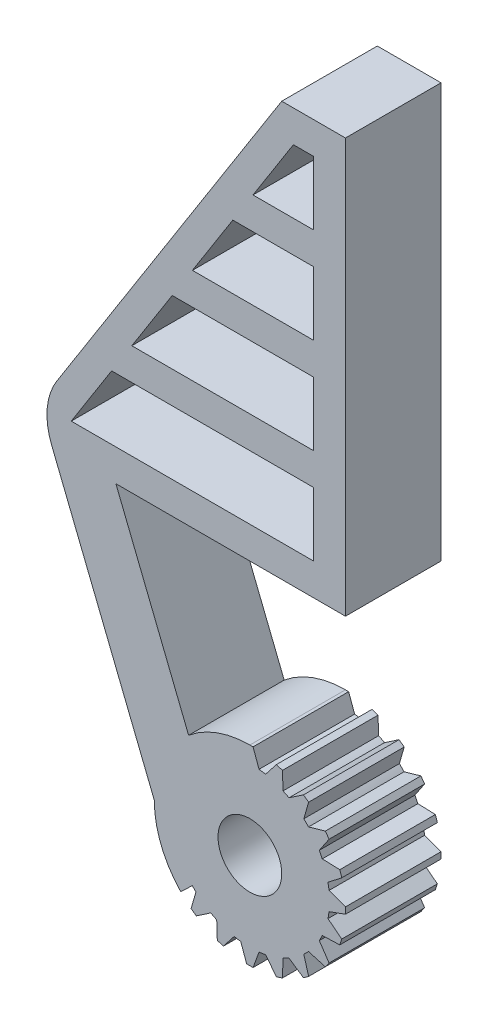
SolidWorks part; units mm, degrees
ref_plane "Front Plane" through (0, 0, 0) normal (0, 0, 1) x (1, 0, 0)
ref_plane "Top Plane" through (0, 0, 0) normal (0, 1, 0) x (1, 0, 0)
ref_plane "Right Plane" through (0, 0, 0) normal (1, 0, 0) x (0, 0, -1)
sketch "Sketch1" plane through (0, 0, 0) normal (0, 0, 1) x (1, 0, 0)
  line L0 (0, 0) -> (0, -120) construction
  line L1 (0, 0) -> (0, -10)
  line L2 (0, -50) -> (0, -60)
  line L5 (-48.033, -60) -> (-30, -105)
  line L7 (-36.0294, -65) -> (-20, -105)
  line L9 (-30, -105) -> (-20, -105)
  line L10 (0, 0) -> (0, -60)
  line L11 (-5, -60) -> (-43.033, -60)
  line L12 (0, 0) -> (-10, 0)
  line L13 (-8.1694, -5) -> (-14.5083, -15)
  line L14 (-5, -5) -> (-5, -15)
  line L15 (-5, -15) -> (-14.5083, -15)
  line L16 (-5, -20) -> (-5, -30)
  line L17 (-17.6777, -20) -> (-5, -20)
  line L18 (-24.0165, -30) -> (-5, -30)
  line L19 (-10, 0) -> (-48.033, -60)
  line L20 (-5, -50) -> (-5, -60)
  line L21 (-5, -35) -> (-27.1859, -35)
  line L22 (-33.5248, -45) -> (-5, -45)
  line L23 (-5, -5) -> (-8.1694, -5)
  line L24 (-5, -50) -> (-36.6942, -50)
  line L25 (0, -60) -> (0, -65)
  line L26 (0, -65) -> (-46.0294, -65)
  line L27 (-17.6777, -20) -> (-24.0165, -30)
  line L28 (-5, -35) -> (-5, -45)
  line L29 (-27.1859, -35) -> (-33.5248, -45)
  line L30 (-36.6942, -50) -> (-43.033, -60)
  circle A2 centre (-15, -105) radius 15
  circle A3 centre (-15, -105) radius 5
  point P27 (-9.7541, -15)
  dimension "D2" = 5
  dimension "D5" = 15
  dimension "D6" = 15
  dimension "D4" = 120
  dimension "D7" = 5
  dimension "D8" = 15
  dimension "D11" = 5
  dimension "D12" = 5
extrude "Boss-Extrude1" add sketch "Sketch1" along normal blind 15
sketch "Sketch2" plane through (0, 0, 15) normal (0, 0, 1) x (1, 0, 0)
  line L0 (-15, -90) -> (-15, -92.5)
  line L1 (-25.8458, -115.3619) -> (-24.0381, -113.6349)
  arc A0 (-25.8458, -115.3619) -> (-15, -90) centre (-15, -105) ccw
  arc A1 (-24.0381, -113.6349) -> (-15, -92.5) centre (-15, -105) ccw
  dimension "D1" = 2.5
  dimension "D2" = 30
extrude "Cut-Extrude1" cut sketch "Sketch2" against normal blind 15
sketch "Sketch3" plane through (0, 0, 15) normal (0, 0, 1) x (1, 0, 0)
  line L0 (-15, -90) -> (-14.5, -90)
  line L3 (-15, -92.75) -> (-15, -90)
  line L4 (-15, -92.75) -> (-13.5, -92.75)
  line L5 (-13.5, -92.75) -> (-14.5, -90)
  line L7 (-12.6411, -92.886) -> (-9.788, -93.8131)
  line L8 (-9.788, -93.8131) -> (-9.8892, -90.8887)
  line L9 (-10.8403, -90.5796) -> (-9.8892, -90.8887)
  line L10 (-12.6411, -92.886) -> (-10.8403, -90.5796)
  line L11 (-9.0132, -94.2079) -> (-6.5861, -95.9712)
  line L12 (-6.5861, -95.9712) -> (-5.7787, -93.1586)
  line L13 (-6.5877, -92.5709) -> (-5.7787, -93.1586)
  line L14 (-9.0132, -94.2079) -> (-6.5877, -92.5709)
  line L15 (-5.9712, -96.5861) -> (-4.2079, -99.0132)
  line L16 (-4.2079, -99.0132) -> (-2.5709, -96.5877)
  line L17 (-3.1586, -95.7787) -> (-2.5709, -96.5877)
  line L18 (-5.9712, -96.5861) -> (-3.1586, -95.7787)
  line L19 (-3.8131, -99.788) -> (-2.886, -102.6411)
  line L20 (-2.886, -102.6411) -> (-0.5796, -100.8403)
  line L21 (-0.8887, -99.8892) -> (-0.5796, -100.8403)
  line L22 (-3.8131, -99.788) -> (-0.8887, -99.8892)
  line L23 (-2.75, -103.5) -> (-2.75, -106.5)
  line L24 (-2.75, -106.5) -> (0, -105.5)
  line L25 (0, -104.5) -> (0, -105.5)
  line L26 (-2.75, -103.5) -> (0, -104.5)
  line L27 (-2.886, -107.3589) -> (-3.8131, -110.212)
  line L28 (-3.8131, -110.212) -> (-0.8887, -110.1108)
  line L29 (-0.5796, -109.1597) -> (-0.8887, -110.1108)
  line L30 (-2.886, -107.3589) -> (-0.5796, -109.1597)
  line L31 (-4.2079, -110.9868) -> (-5.9712, -113.4139)
  line L32 (-5.9712, -113.4139) -> (-3.1586, -114.2213)
  line L33 (-2.5709, -113.4123) -> (-3.1586, -114.2213)
  line L34 (-4.2079, -110.9868) -> (-2.5709, -113.4123)
  line L35 (-6.5861, -114.0288) -> (-9.0132, -115.7921)
  line L36 (-9.0132, -115.7921) -> (-6.5877, -117.4291)
  line L37 (-5.7787, -116.8414) -> (-6.5877, -117.4291)
  line L38 (-6.5861, -114.0288) -> (-5.7787, -116.8414)
  line L39 (-9.788, -116.1869) -> (-12.6411, -117.114)
  line L40 (-12.6411, -117.114) -> (-10.8403, -119.4204)
  line L41 (-9.8892, -119.1113) -> (-10.8403, -119.4204)
  line L42 (-9.788, -116.1869) -> (-9.8892, -119.1113)
  line L43 (-13.5, -117.25) -> (-16.5, -117.25)
  line L44 (-16.5, -117.25) -> (-15.5, -120)
  line L45 (-14.5, -120) -> (-15.5, -120)
  line L46 (-13.5, -117.25) -> (-14.5, -120)
  line L47 (-17.3589, -117.114) -> (-20.212, -116.1869)
  line L48 (-20.212, -116.1869) -> (-20.1108, -119.1113)
  line L49 (-19.1597, -119.4204) -> (-20.1108, -119.1113)
  line L50 (-17.3589, -117.114) -> (-19.1597, -119.4204)
  line L51 (-20.9868, -115.7921) -> (-23.4139, -114.0288)
  line L52 (-23.4139, -114.0288) -> (-24.2213, -116.8414)
  line L53 (-23.4123, -117.4291) -> (-24.2213, -116.8414)
  line L54 (-20.9868, -115.7921) -> (-23.4123, -117.4291)
  line L55 (-24.0288, -113.4139) -> (-25.7921, -110.9868)
  line L56 (-25.7921, -110.9868) -> (-25.8915, -111.134)
  line L58 (-24.0288, -113.4139) -> (-24.1994, -113.4629)
  line L59 (-26.1869, -110.212) -> (-27.114, -107.3589)
  line L60 (-27.114, -107.3589) -> (-27.2539, -107.4681)
  line L62 (-26.1869, -110.212) -> (-26.3644, -110.2059)
  line L63 (-27.25, -106.5) -> (-27.25, -103.5)
  line L64 (-27.25, -103.5) -> (-27.4169, -103.5607)
  line L66 (-27.25, -106.5) -> (-27.4169, -106.4393)
  line L67 (-27.114, -102.6411) -> (-26.1869, -99.788)
  line L68 (-26.1869, -99.788) -> (-26.3644, -99.7941)
  line L70 (-27.114, -102.6411) -> (-27.2539, -102.5319)
  line L71 (-25.7921, -99.0132) -> (-24.0288, -96.5861)
  line L72 (-24.0288, -96.5861) -> (-24.1994, -96.5371)
  line L74 (-25.7921, -99.0132) -> (-25.8915, -98.866)
  line L83 (-27.4291, -96.5877) -> (-26.8414, -95.7787) [skipped]
  line L84 (-24.2213, -93.1586) -> (-23.4123, -92.5709) [skipped]
  line L85 (-20.1108, -90.8887) -> (-19.1597, -90.5796) [skipped]
  line L86 (-29.4204, -100.8403) -> (-29.1113, -99.8892) [skipped]
  line L87 (-30, -105.5) -> (-30, -104.5) [skipped]
  line L88 (-26.8414, -114.2213) -> (-27.4291, -113.4123) [skipped]
  line L89 (-29.1113, -110.1108) -> (-29.4204, -109.1597) [skipped]
  line L90 (-17.3589, -92.886) -> (-17.4681, -92.7461) [skipped]
  line L91 (-20.212, -93.8131) -> (-17.3589, -92.886) [skipped]
  line L92 (-20.9868, -94.2079) -> (-21.134, -94.1085) [skipped]
  line L93 (-23.4139, -95.9712) -> (-20.9868, -94.2079) [skipped]
  circle A0 centre (-15, -105) radius 12.5
  arc M18 (-24.0381, -113.6349) -> (-15, -92.5) centre (-15, -105) ccw
  line M19 (-15, -92.5) -> (-15, -90)
  dimension "D1" = 20
extrude "Boss-Extrude2" add sketch "Sketch3" against normal blind 15 contours L3 A0 L72 L71 L74 L68 L67 L70 L64 L63 L66 L60 L59 L62 L56 L55 L58 L52 L51 L54 L48 L47 L50 L44 L43 L46 L40 L39 L42 L36 L35 L38 L32 L31 L34 L28 L27 L30 M18 | L18 L16 L17 M18 | L5 L0 M18 M19 | L22 L20 L21 M18 | L10 L8 L9 M18 | L26 L24 L25 M18 | L14 L12 L13 M18 | L30 L28 L29 M18 | L34 L32 L33 M18 | L38 L36 L37 M18 | L46 L44 L45 M18 | L54 L52 L53 M18
fillet "Fillet1" radius 10 1 edges at (-48.033, -60, 7.5)
